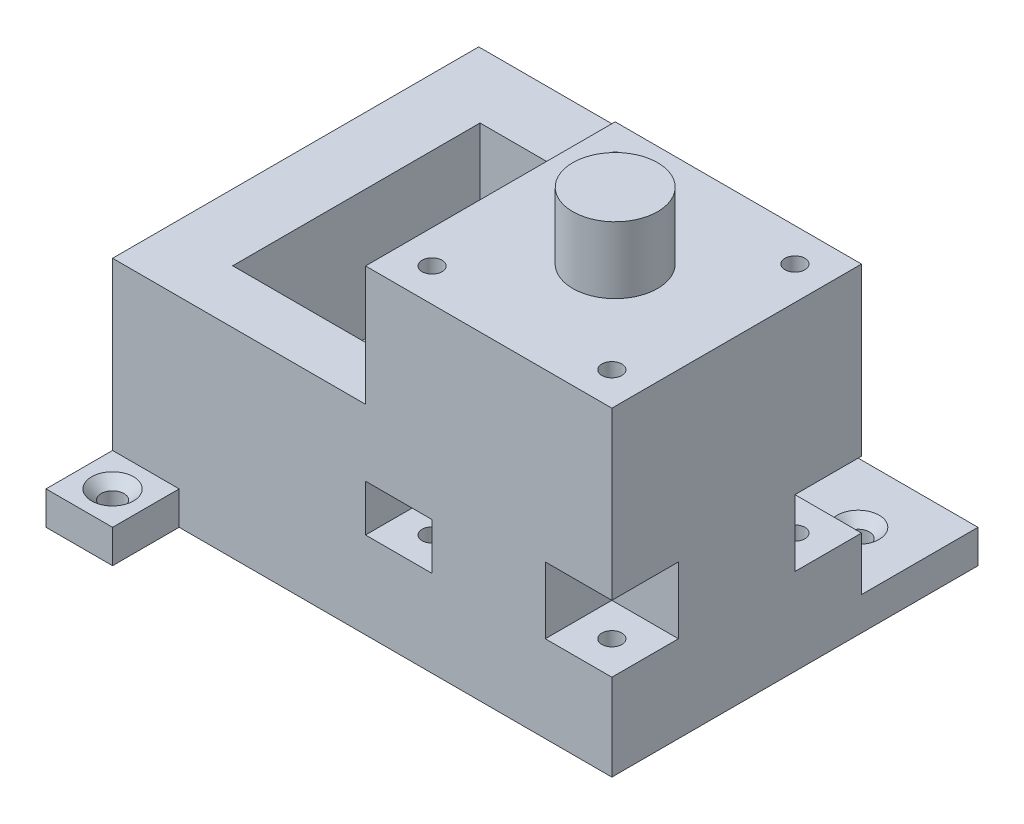
SolidWorks part; units mm, degrees
ref_plane "Plan de face" through (0, 0, 0) normal (0, 0, 1) x (1, 0, 0)
ref_plane "Plan de dessus" through (0, 0, 0) normal (0, 1, 0) x (1, 0, 0)
ref_plane "Plan de droite" through (0, 0, 0) normal (1, 0, 0) x (0, 0, -1)
sketch "Esquisse3" plane through (0, 0, 0) normal (0, 1, 0) x (1, 0, 0)
  line L0 (0, 0) -> (0, 55)
  line L1 (0, 55) -> (38, 55)
  line L2 (38, 55) -> (38, 37.5)
  line L3 (38, 37.5) -> (75, 37.5)
  line L4 (75, 37.5) -> (75, 0)
  line L5 (75, 0) -> (0, 0)
  dimension "D1" = 55
  dimension "D2" = 38
  dimension "D3" = 37.5
  dimension "D4" = 37
  dimension "D5" = 75
extrude "Boss.-Extru.1" add sketch "Esquisse3" along normal blind 30
sketch "Esquisse6" plane through (0, 30, 0) normal (0, 1, 0) x (1, 0, 0)
  line L0 (0, 0) -> (75, 0) construction
  line L1 (75, 37.5) -> (38, 37.5)
  line L2 (75, 37.5) -> (75, 0)
  line L3 (75, 0) -> (38, 0)
  line L4 (38, 37.5) -> (38, 0)
  dimension "D1" = 37
extrude "Boss.-Extru.4" add sketch "Esquisse6" along normal blind 18
sketch "Esquisse7" plane through (0, 48, 0) normal (0, 1, 0) x (1, 0, 0)
  line L0 (75, 37.5) -> (38, 37.5) construction
  line L1 (75, 0) -> (75, 37.5) construction
  circle A0 centre (56.5, 19) radius 6.375
  dimension "D3" = 12.75
  dimension "D1" = 18.5
  dimension "D2" = 18.5
extrude "Boss.-Extru.5" add sketch "Esquisse7" along normal blind 10
sketch "Esquisse8" plane through (0, 48, 0) normal (0, 1, 0) x (1, 0, 0)
  line L0 (75, 0) -> (75, 37.5) construction
  line L2 (75, 37.5) -> (38, 37.5) construction
  line L3 (38, 0) -> (75, 0) construction
  line L4 (38, 37.5) -> (38, 0) construction
  line L5 (38, 37.5) -> (38, 0) construction
  circle A0 centre (43, 32.5) radius 1.5
  circle A1 centre (70, 32.5) radius 1.5
  circle A2 centre (70, 5) radius 1.5
  circle A3 centre (43, 5) radius 1.5
  dimension "D2" = 5
  dimension "D9" = 3
  dimension "D10" = 3
  dimension "D11" = 3
  dimension "D12" = 3
  dimension "D1" = 5
  dimension "D3" = 5
  dimension "D4" = 5
  dimension "D5" = 5
  dimension "D6" = 5
  dimension "D7" = 5
  dimension "D8" = 5
extrude "Enlèv. mat.-Extru.1" cut sketch "Esquisse8" against normal blind 43
sketch "Esquisse9" plane through (75, 0, 0) normal (1, 0, 0) x (0, 0, -1)
  line L0 (0, 48) -> (0, 0) construction
  line L1 (0, 13) -> (10, 13)
  line L2 (0, 13) -> (0, 23)
  line L3 (0, 23) -> (10, 23)
  line L4 (10, 13) -> (10, 23)
  line L6 (0, 48) -> (37.5, 48) construction
  line L7 (37.5, 48) -> (37.5, 0) construction
  line L8 (37.5, 13) -> (27.5, 13)
  line L9 (37.5, 13) -> (37.5, 23)
  line L10 (37.5, 23) -> (27.5, 23)
  line L11 (27.5, 13) -> (27.5, 23)
  dimension "D1" = 25
  dimension "D2" = 10
  dimension "D3" = 10
  dimension "D4" = 25
  dimension "D5" = 10
  dimension "D6" = 10
extrude "Enlèv. mat.-Extru.2" cut sketch "Esquisse9" against normal blind 10
sketch "Esquisse10" plane through (0, 0, -37.5) normal (0, 0, -1) x (-1, 0, 0)
  line L0 (-38, 48) -> (-38, 30) construction
  line L1 (-38, 20) -> (-48, 20)
  line L2 (-38, 20) -> (-38, 13)
  line L3 (-38, 13) -> (-48, 13)
  line L4 (-48, 20) -> (-48, 13)
  line L5 (-75, 48) -> (-38, 48) construction
  dimension "D1" = 28
  dimension "D2" = 7
  dimension "D3" = 10
extrude "Enlèv. mat.-Extru.5" cut sketch "Esquisse10" against normal blind 10
sketch "Esquisse11" plane through (0, 0, 0) normal (0, 0, 1) x (1, 0, 0)
  line L0 (38, 48) -> (38, 30) construction
  line L1 (38, 20) -> (48, 20)
  line L2 (38, 20) -> (38, 13)
  line L3 (38, 13) -> (48, 13)
  line L4 (48, 20) -> (48, 13)
  line L5 (38, 48) -> (75, 48) construction
  dimension "D1" = 28
  dimension "D2" = 7
  dimension "D3" = 10
extrude "Enlèv. mat.-Extru.6" cut sketch "Esquisse11" against normal blind 10
sketch "Esquisse12" plane through (0, 30, 0) normal (0, 1, 0) x (1, 0, 0)
  line L0 (75, 0) -> (75, 37.5) construction
  line L1 (10, 45.1988) -> (30, 45.1988)
  line L2 (10, 45.1988) -> (10, 8.0441)
  line L3 (10, 8.0441) -> (30, 8.0441)
  line L4 (30, 45.1988) -> (30, 8.0441)
  dimension "D1" = 45
  dimension "D2" = 20
extrude "Enlèv. mat.-Extru.7" cut sketch "Esquisse12" against normal blind 19.44
sketch "Esquisse13" plane through (0, 0, -45.1988) normal (0, 0, 1) x (1, 0, 0)
  line L0 (30, 10.56) -> (10, 10.56) construction
  line L1 (15, 10.56) -> (25, 10.56)
  line L2 (15, 10.56) -> (15, 20.56)
  line L3 (15, 20.56) -> (25, 20.56)
  line L4 (25, 10.56) -> (25, 20.56)
  dimension "D1" = 5
  dimension "D2" = 5
  dimension "D3" = 10
extrude "Enlèv. mat.-Extru.8" cut sketch "Esquisse13" against normal up to surface (9.8012 mm away) up to face at (19, 15, -55)
sketch "Esquisse14" plane through (0, 0, 0) normal (0, -1, 0) x (1, 0, 0)
  line L0 (38, -55) -> (0, -55) construction
  line L1 (38, -37.5) -> (75, -37.5)
  line L2 (38, -37.5) -> (38, -55)
  line L3 (38, -55) -> (75, -55)
  line L4 (75, -37.5) -> (75, -55)
  line L5 (75, 0) -> (75, -37.5) construction
extrude "Boss.-Extru.6" add sketch "Esquisse14" against normal blind 5
sketch "Esquisse15" plane through (0, 0, 0) normal (0, -1, 0) x (1, 0, 0)
  line L1 (0, 0) -> (10, 0)
  line L2 (0, 0) -> (0, 10)
  line L3 (0, 10) -> (10, 10)
  line L4 (10, 0) -> (10, 10)
  dimension "D1" = 10
  dimension "D2" = 10
sketch "Esquisse20" plane through (0, 0, 0) normal (0, 0, 1) x (1, 0, 0)
  line L1 (0, 0) -> (10, 0)
  line L2 (0, 0) -> (0, 5)
  line L3 (0, 5) -> (10, 5)
  line L4 (10, 0) -> (10, 5)
  dimension "D1" = 5
  dimension "D2" = 10
extrude "Boss.-Extru.8" add sketch "Esquisse20" along normal blind 10
sketch "Esquisse21" plane through (0, 5, 0) normal (0, 1, 0) x (1, 0, 0)
  line L0 (0, 0) -> (38, 0) construction
  line L3 (10, 0) -> (10, -10) construction
  line L4 (38, 55) -> (75, 55) construction
  line L5 (38, 37.5) -> (38, 55) construction
  line L6 (75, 55) -> (75, 37.5) construction
  circle A0 centre (5, -5) radius 1.5
  circle A1 centre (47, 46) radius 1.5
  circle A2 centre (66, 46) radius 1.5
  dimension "D1" = 5
  dimension "D3" = 3
  dimension "D6" = 3
  dimension "D8" = 3
  dimension "D2" = 5
  dimension "D4" = 9
  dimension "D5" = 9
  dimension "D7" = 9
  dimension "D9" = 9
hole_wizard "Fraisage pour vis à tête fraisée bombée M32" positions "Esquisse22" profile "Esquisse23" countersink size "M3" standard "ISO"
sketch "Esquisse22" plane through (0, 5, 0) normal (0, 1, 0) x (1, 0, 0)
  point P0 (5, -5)
  point P3 (47, 46)
  point P6 (66, 46)
sketch "Esquisse23" plane through (5, 5, 5) normal (1, 0, 0) x (0, 0, 1)
  line L0 (0, 0) -> (0, 6.0215)
  line L1 (0, 6.0215) -> (1.7, 5)
  line L2 (1.7, 5) -> (1.7, 1.45)
  line L3 (1.7, 1.45) -> (3.15, 0)
  line L5 (3.15, 0) -> (0, 0)
  line L6 (-1.7, 1.45) -> (-3.15, 0) construction
  line L10 (0, 6.0215) -> (-1.7, 5) construction
  line L11 (0, -6.35) -> (0, 107.95) construction
  dimension "Diamètre du perçage" = 3.4
  dimension "Profondeur du perçage" = 5
  dimension "Diamètre du fraisage entrant" = 6.3
  dimension "Angle du fraisage entrant" = 90
  dimension "Angle de pointe" = 118
